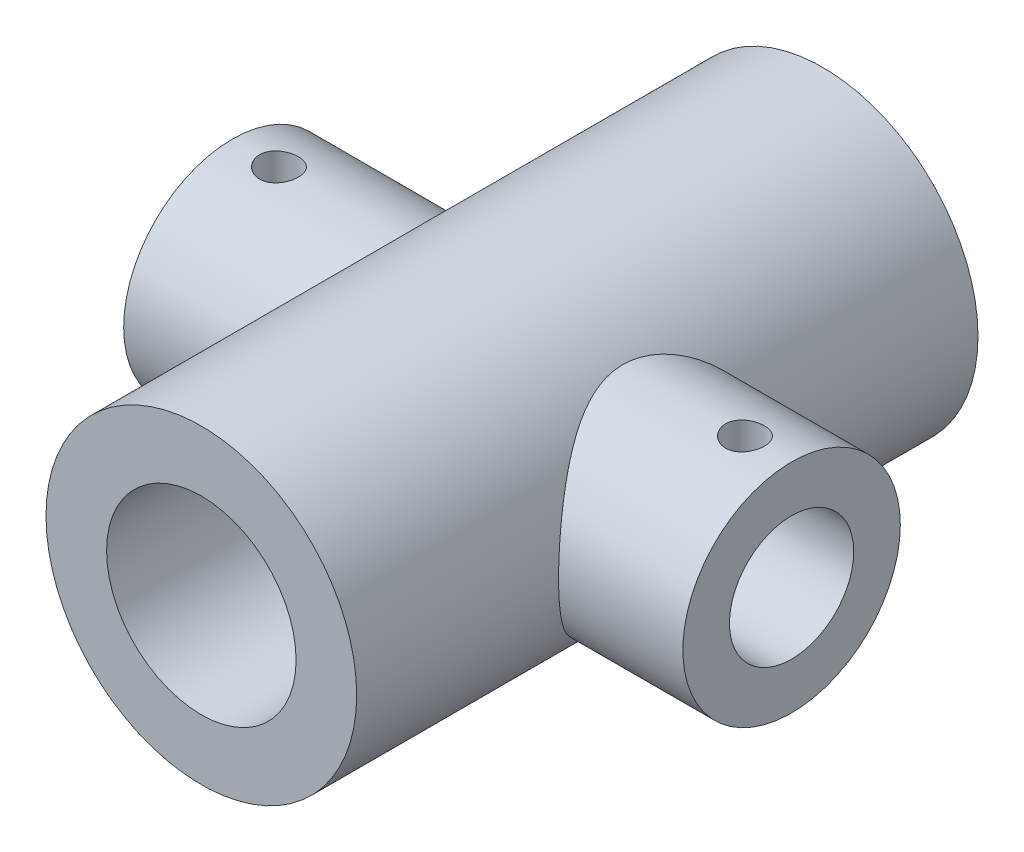
SolidWorks part; units mm, degrees
ref_plane "Front Plane" through (0, 0, 0) normal (0, 0, 1) x (1, 0, 0)
ref_plane "Top Plane" through (0, 0, 0) normal (0, 1, 0) x (1, 0, 0)
ref_plane "Right Plane" through (0, 0, 0) normal (1, 0, 0) x (0, 0, -1)
sketch "Sketch1" plane through (0, 0, 0) normal (0, 0, 1) x (1, 0, 0)
  circle A0 centre (0, 0) radius 10
  circle A1 centre (0, 0) radius 6.1
  dimension "D1" = 20
  dimension "D2" = 12.2
extrude "Boss-Extrude1" add sketch "Sketch1" along normal mid plane 40
ref_plane "Plane1" through (18, 0, 0) normal (1, 0, 0) x (0, 0, -1)
sketch "Sketch3" plane through (18, 0, 0) normal (1, 0, 0) x (0, 0, -1)
  circle A0 centre (0, 0) radius 4
  circle A1 centre (0, 0) radius 7
  dimension "D1" = 14
  dimension "D2" = 8
extrude "Boss-Extrude2" add sketch "Sketch3" against normal up to surface (8 mm away) up to face at (10, 0, 20)
mirror "Mirror2" about plane through (0, 0, 0) normal (1, 0, 0) of "Boss-Extrude2"
ref_plane "Plane3" through (0, 7, 0) normal (0, 1, 0) x (1, 0, 0)
hole_wizard "M3 Tapped Hole2" positions "Sketch7" profile "Sketch8" tap size "M3" standard "DIN"
sketch "Sketch7" plane through (0, 7, 0) normal (0, 1, 0) x (1, 0, 0)
  line L0 (-18, 7) -> (-18, -7) construction
  line L1 (18, -7) -> (18, 7) construction
  point P0 (-15, 0)
  point P2 (15, 0)
  point P9 (0, 0)
  dimension "D1" = 3
  dimension "D2" = 3
sketch "Sketch8" plane through (-15, 7, 0) normal (1, 0, 0) x (0, 0, 1)
  line L0 (0, 0) -> (0, 9.2511)
  line L1 (0, 9.2511) -> (1.25, 8.5)
  line L2 (1.25, 8.5) -> (1.25, 0)
  line L5 (1.25, 0) -> (0, 0)
  line L10 (0, 9.2511) -> (-1.25, 8.5) construction
  line L11 (0, -6.35) -> (0, 107.95) construction
  dimension "Tap Drill Dia." = 2.5
  dimension "Tap Drill Depth" = 8.5
  dimension "Drill Angle" = 118
cosmetic thread "Hole Thread2"
cosmetic thread "Hole Thread3"
